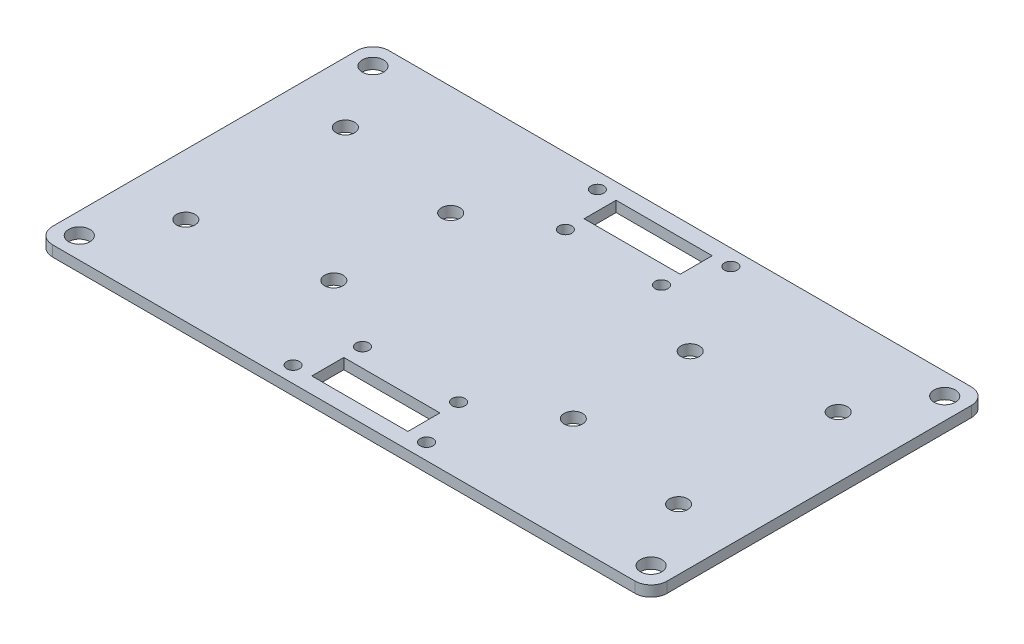
SolidWorks part; units mm, degrees
ref_plane "Plano frontal" through (0, 0, 0) normal (0, 0, 1) x (1, 0, 0)
ref_plane "Plano superior" through (0, 0, 0) normal (0, 1, 0) x (1, 0, 0)
ref_plane "Plano direito" through (0, 0, 0) normal (1, 0, 0) x (0, 0, -1)
sketch "Esboço1" plane through (0, 0, 0) normal (0, 1, 0) x (1, 0, 0)
  line L7 (-57.5484, 31.5) -> (57.5484, 31.5)
  line L8 (57.5484, 31.5) -> (57.5484, -31.5)
  line L9 (57.5484, -31.5) -> (-57.5484, -31.5)
  line L10 (-57.5484, -31.5) -> (-57.5484, 31.5)
  line L11 (0, 31.5) -> (0, -31.5) construction
  line L12 (-57.5484, 0) -> (57.5484, 0) construction
  dimension "D1" = 63
  dimension "D2" = 115.0968
extrude "Ressalto-extrusão1" add sketch "Esboço1" along normal blind 2
sketch "Esboço2" plane through (0, 2, 0) normal (0, 1, 0) x (1, 0, 0)
  line L0 (-57.5484, 0) -> (57.5484, 0) construction
  line L1 (-57.5484, 31.5) -> (-57.5484, -31.5) construction
  line L2 (-57.5484, -31.5) -> (57.5484, -31.5) construction
  line L5 (57.5484, -31.5) -> (57.5484, 31.5) construction
  line L6 (0, -31.5) -> (0, 31.5) construction
  line L7 (57.5484, 31.5) -> (-57.5484, 31.5) construction
  circle A8 centre (-46.1536, -14.945) radius 1.73
  circle A10 centre (-22.4284, -10.945) radius 1.73
  circle A11 centre (22.4284, -10.945) radius 1.73
  circle A12 centre (46.1536, -14.945) radius 1.73
  circle A13 centre (46.1536, 14.945) radius 1.73
  circle A14 centre (22.4284, 10.945) radius 1.73
  circle A15 centre (-22.4284, 10.945) radius 1.73
  circle A16 centre (-46.1536, 14.945) radius 1.73
  dimension "D1" = 16.555
  dimension "D3" = 3.46
  dimension "D2" = 24.06
extrude "Corte-extrusão1" cut sketch "Esboço2" against normal through all
sketch "Esboço3" plane through (0, 0, 0) normal (0, -1, 0) x (1, 0, 0)
  line L0 (0, 31.5) -> (0, 28.5) construction
  line L1 (-57.5484, 31.5) -> (57.5484, 31.5) construction
  line L2 (-9, 28.5) -> (9, 28.5)
  line L3 (9, 28.5) -> (9, 22.5)
  line L4 (-9, 28.5) -> (-9, 22.5)
  line L5 (-9, 22.5) -> (9, 22.5)
  line L6 (-57.5484, 0) -> (57.5484, 0) construction
  line L7 (-57.5484, -31.5) -> (-57.5484, 31.5) construction
  line L8 (57.5484, 31.5) -> (57.5484, -31.5) construction
  line L9 (9, 28.5) -> (9, 22.5)
  line L10 (-9, 28.5) -> (-9, 22.5)
  line L11 (9, 28.5) -> (9, 22.5)
  line L12 (-9, 28.5) -> (-9, 22.5)
  line L13 (9, 28.5) -> (9, 22.5)
  line L14 (-9, 28.5) -> (-9, 22.5)
  line L15 (0, -31.5) -> (0, -28.5) construction
  line L16 (-9, -28.5) -> (-9, -22.5)
  line L17 (9, -28.5) -> (9, -22.5)
  line L18 (-9, -28.5) -> (-9, -22.5)
  line L19 (9, -28.5) -> (9, -22.5)
  line L20 (-9, -28.5) -> (-9, -22.5)
  line L21 (9, -28.5) -> (9, -22.5)
  line L22 (-9, -22.5) -> (9, -22.5)
  line L23 (-9, -28.5) -> (-9, -22.5)
  line L24 (9, -28.5) -> (9, -22.5)
  line L25 (-9, -28.5) -> (9, -28.5)
  point P8 (0, 28.5)
  point P22 (0, -28.5)
  dimension "D1" = 3
  dimension "D2" = 18
  dimension "D3" = 6
extrude "Corte-extrusão2" cut sketch "Esboço3" against normal through all contours L4 L5 L3 L2 | L16 L25 L17 L22
sketch "Esboço5" plane through (0, 2, 0) normal (0, 1, 0) x (1, 0, 0)
  line L2 (57.5484, 31.5) -> (-57.5484, 31.5) construction
  line L3 (57.5484, -31.5) -> (57.5484, 31.5) construction
  line L4 (57.5484, 0) -> (-57.5484, 0) construction
  line L5 (-57.5484, 31.5) -> (-57.5484, -31.5) construction
  line L6 (0, 31.5) -> (0, -31.5) construction
  line L7 (-57.5484, -31.5) -> (57.5484, -31.5) construction
  line L8 (53.5484, -13.175) -> (53.5484, -27.5) construction
  line L9 (-53.5484, -13.175) -> (-53.5484, -27.5) construction
  line L10 (-53.5484, 21.175) -> (-53.5484, 35.5) construction
  circle A0 centre (53.5484, 27.5) radius 2
  circle A1 centre (53.5484, -27.5) radius 2
  circle A2 centre (-53.5484, -27.5) radius 2
  circle A3 centre (-53.5484, 27.5) radius 2
  dimension "D2" = 4
  dimension "D1" = 4
  dimension "D3" = 4
extrude "Corte-extrusão3" cut sketch "Esboço5" against normal through all
fillet "Filete1" radius 3 4 edges at (57.5484, 1, -31.5) (57.5484, 1, 31.5) (-57.5484, 1, 31.5) (-57.5484, 1, -31.5)
sketch "Esboço8" plane through (0, 2, 0) normal (0, 1, 0) x (1, 0, 0)
  line L0 (-57.5484, 28.5) -> (-57.5484, -28.5) construction
  line L1 (54.5484, 31.5) -> (-54.5484, 31.5) construction
  line L2 (0, 0) -> (0, 31.5) construction
  line L3 (57.5484, 0) -> (-57.5484, 0) construction
  line L4 (-54.5484, -31.5) -> (54.5484, -31.5) construction
  line L5 (57.5484, -28.5) -> (57.5484, 28.5) construction
  circle A0 centre (-12.4984, 28.5) radius 1.2
  circle A1 centre (12.4984, 28.5) radius 1.2
  circle A2 centre (12.4984, -28.5) radius 1.2
  circle A3 centre (-12.4984, -28.5) radius 1.2
  circle A8 centre (-8.9984, -19) radius 1.2
  circle A12 centre (8.9984, -19) radius 1.2
  circle A13 centre (8.9984, 19) radius 1.2
  circle A14 centre (-8.9984, 19) radius 1.2
  dimension "D1" = 2.4
  dimension "D4" = 2.4
  dimension "D5" = 12.5
  dimension "D6" = 48.55
  dimension "D2" = 45.05
  dimension "D3" = 3
extrude "Corte-extrusão4" cut sketch "Esboço8" against normal through all
